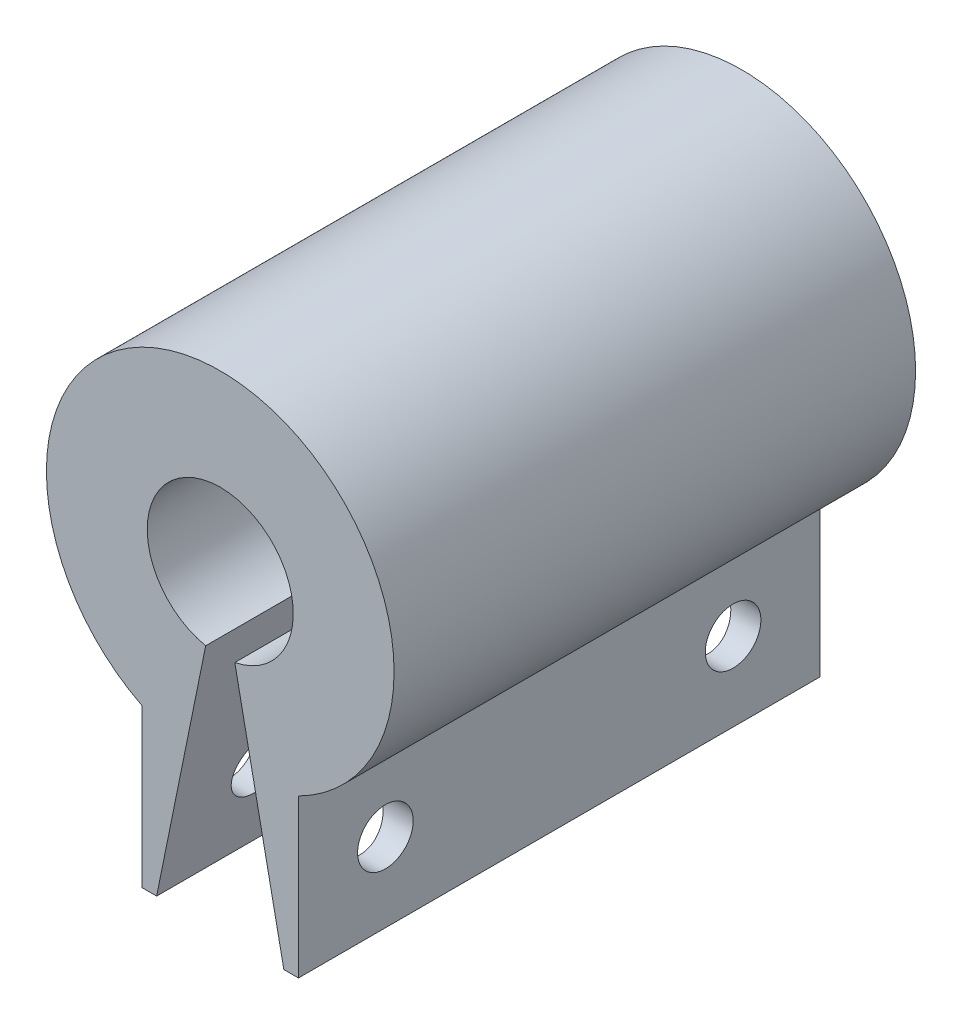
SolidWorks part; units mm, degrees
ref_plane "正面" through (0, 0, 0) normal (0, 0, 1) x (1, 0, 0)
ref_plane "平面" through (0, 0, 0) normal (0, 1, 0) x (1, 0, 0)
ref_plane "右側面" through (0, 0, 0) normal (1, 0, 0) x (0, 0, -1)
sketch "ｽｹｯﾁ1" plane through (0, 0, 0) normal (0, 0, 1) x (1, 0, 0)
  line L2 (-4.5, -8.9303) -> (-4.5, -18)
  line L3 (-4.5, -18) -> (4.5, -18)
  line L4 (4.5, -8.9303) -> (4.5, -18)
  arc A0 (4.5, -8.9303) -> (-4.5, -8.9303) centre (0, 0) ccw
  point P8 (0, -18)
  dimension "D1" = 20
  dimension "D2" = 9
  dimension "D3" = 18
extrude "ﾎﾞｽ - 押し出し1" add sketch "ｽｹｯﾁ1" along normal blind 30
sketch "ｽｹｯﾁ2" plane through (0, 0, 30) normal (0, 0, 1) x (1, 0, 0)
  circle A0 centre (0, 0) radius 4.2
  dimension "D1" = 8.4
extrude "ｶｯﾄ - 押し出し1" cut sketch "ｽｹｯﾁ2" against normal blind 15
sketch "ｽｹｯﾁ3" plane through (0, 0, 0) normal (0, 0, -1) x (-1, 0, 0)
  circle A0 centre (0, 0) radius 1.175
  dimension "D1" = 2.35
extrude "ｶｯﾄ - 押し出し2" cut sketch "ｽｹｯﾁ3" against normal blind 15
sketch "ｽｹｯﾁ4" plane through (0, 0, 30) normal (0, 0, 1) x (1, 0, 0)
  line L9 (-4.5, -18) -> (4.5, -18) construction
  line L10 (-0.234, -1.1515) -> (-3.6587, -18)
  line L11 (0.234, -1.1515) -> (3.6587, -18)
  arc A0 (-3.6587, -18) -> (3.6587, -18) centre (0, 0) ccw
  circle A1 centre (0, 0) radius 1.175 construction
  arc A2 (-0.234, -1.1515) -> (0.234, -1.1515) centre (0, 0) ccw
  point P5 (-0.234, -1.1515)
  point P6 (0.234, -1.1515)
  point P7 (0, -18.3681)
  dimension "D1" = 0.4712
sketch "ｽｹｯﾁ10" plane through (4.5, 0, 0) normal (1, 0, 0) x (0, 0, -1)
  line L0 (-30, -18) -> (-30, -8.9303) construction
  line L1 (0, -18) -> (0, -8.9303) construction
  circle A0 centre (-25, -13.4651) radius 1.6
  circle A1 centre (-5, -13.4651) radius 1.6
  point P9 (-30, -13.4651)
  dimension "D3" = 3.2
  dimension "D1" = 5
  dimension "D2" = 5
extrude "ｶｯﾄ - 押し出し8" cut sketch "ｽｹｯﾁ10" against normal through all
extrude "ｶｯﾄ - 押し出し9" cut sketch "ｽｹｯﾁ4" against normal through all
equation "\"D1@ｽｹｯﾁ4\"=PI*(2.35-2.2)"
